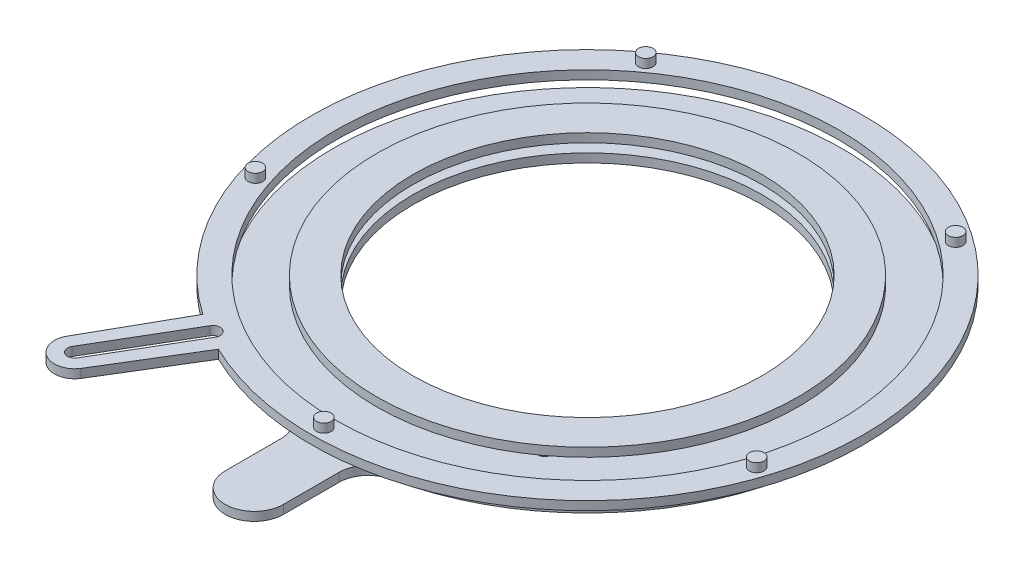
SolidWorks part; units mm, degrees
ref_plane "前视基准面" through (0, 0, 0) normal (0, 0, 1) x (1, 0, 0)
ref_plane "上视基准面" through (0, 0, 0) normal (0, 1, 0) x (1, 0, 0)
ref_plane "右视基准面" through (0, 0, 0) normal (1, 0, 0) x (0, 0, -1)
sketch "草图1" plane through (0, 0, 0) normal (0, 1, 0) x (1, 0, 0)
  circle A0 centre (0, 0) radius 72.5
  circle A1 centre (0, 0) radius 60
  dimension "D1" = 145
  dimension "D2" = 120
extrude "凸台-拉伸1" add sketch "草图1" along normal blind 3
sketch "草图2" plane through (0, 0, 0) normal (0, 1, 0) x (1, 0, 0)
  line L0 (0, 72.5) -> (0, 60) construction
  circle A0 centre (0, 0) radius 72.5 construction
  circle A1 centre (0, 0) radius 60 construction
  circle A2 centre (0, 66.25) radius 2.5
  dimension "D1" = 5
extrude "凸台-拉伸2" add sketch "草图2" against normal blind 3
pattern_circular "阵列(圆周)1" count 5 over 360 about axis through (0, 0, 0) along (0, 1, 0) of "凸台-拉伸2"
sketch "草图3" plane through (0, -3, 0) normal (0, -1, 0) x (1, 0, 0)
  line L0 (0, -41.49) -> (0, 174.9176) construction
  line L1 (10, 114.5871) -> (10, 95.4267)
  line L2 (-10, 114.5871) -> (-10, 95.4267)
  arc A1 (-10, 95.4267) -> (-17.9487, 85.6393) centre (-20, 95.4267) cw
  circle A3 centre (0, 0) radius 60 construction
  circle A4 centre (0, 0) radius 60
  arc A5 (-17.9487, 85.6393) -> (17.9487, 85.6393) centre (0, 0) ccw
  arc A6 (10, 114.5871) -> (-10, 114.5871) centre (0, 114.5871) ccw
  arc A7 (10, 95.4267) -> (17.9487, 85.6393) centre (20, 95.4267) ccw
  dimension "D1" = 175
  dimension "D2" = 20
  dimension "D3" = 10
extrude "凸台-拉伸3" add sketch "草图3" along normal blind 3
sketch "草图4" plane through (0, 0, 0) normal (0, 1, 0) x (1, 0, 0)
  line L0 (0, 0) -> (-61.7761, -105.2374) construction
  line L1 (-65.2234, -111.11) -> (-47.4217, -80.7842) construction
  line L2 (-71.235, -107.5238) -> (-54.4804, -77.826)
  line L3 (-59.3384, -114.9003) -> (-41.398, -85.5056)
  arc A0 (-41.398, -85.5056) -> (-54.4804, -77.826) centre (0, 0) ccw
  circle A1 centre (0, 0) radius 86.5
  arc A2 (-71.235, -107.5238) -> (-59.3384, -114.9003) centre (-65.2234, -111.11) ccw
  point P4 (-56.9387, -95.4474)
  dimension "D1" = 190
  dimension "D2" = 173
  dimension "D3" = 7
extrude "凸台-拉伸4" add sketch "草图4" along normal blind 3 separate body
sketch "草图7" plane through (0, 3, 0) normal (0, 1, 0) x (1, 0, 0)
  circle A0 centre (0, -90.6426) radius 2.5
extrude "凸台-拉伸7" add sketch "草图7" along normal blind 3
pattern_circular "阵列(圆周)5" count 5 over 360 about axis through (0, 0, 0) along (0, 1, 0) of "凸台-拉伸7"
sketch "草图5" plane through (0, 0, 0) normal (0, 1, 0) x (1, 0, 0)
  line L0 (0, -37.3424) -> (0, -102.3161) construction
  line L1 (-2.52, -94.9666) -> (-1.25, -97.9666)
  line L2 (-1.25, -97.9666) -> (1.25, -97.9666)
  line L3 (1.25, -97.9666) -> (2.52, -94.9666)
  line L4 (-2.52, -94.9666) -> (2.52, -94.9666)
  circle A0 centre (0, 0) radius 95 construction
  dimension "D1" = 5.04
  dimension "D2" = 2.5
  dimension "D3" = 3
sketch "草图9" plane through (0, 0, 0) normal (0, 1, 0) x (1, 0, 0)
  line L0 (-65.2234, -111.11) -> (-47.666, -81.2004) construction
  line L1 (0, 0) -> (-61.7761, -105.2374) construction
  line L2 (-67.3794, -109.8444) -> (-49.822, -79.9348)
  line L3 (-63.0675, -112.3756) -> (-45.5101, -82.466)
  arc A1 (-67.3794, -109.8444) -> (-63.0675, -112.3756) centre (-65.2234, -111.11) ccw
  arc A2 (-45.5101, -82.466) -> (-49.822, -79.9348) centre (-47.666, -81.2004) ccw
  point P6 (-56.4447, -96.1552)
  dimension "D1" = 2.5
extrude "切除-拉伸1" cut sketch "草图9" along normal blind 3
